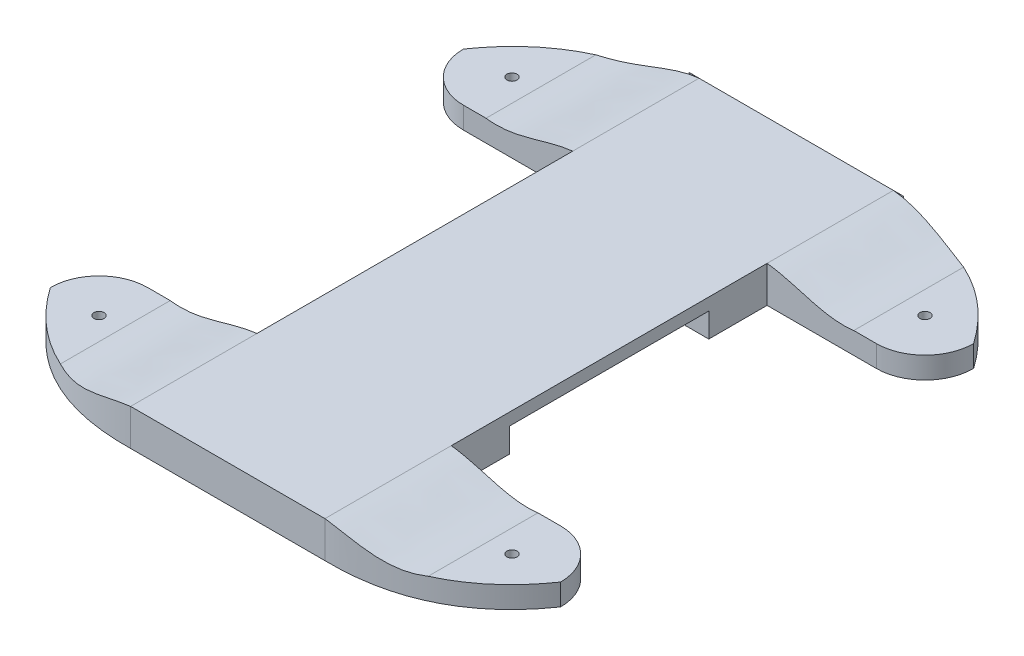
SolidWorks part; units mm, degrees
ref_plane "Front Plane" through (0, 0, 0) normal (0, 0, 1) x (1, 0, 0)
ref_plane "Top Plane" through (0, 0, 0) normal (0, 1, 0) x (1, 0, 0)
ref_plane "Right Plane" through (0, 0, 0) normal (1, 0, 0) x (0, 0, -1)
sketch "Sketch1" plane through (0, 0, 0) normal (0, 1, 0) x (1, 0, 0)
  line L0 (0, -315.44) -> (0, 409.5416) construction
  line L1 (383.7857, 0) -> (-378.4212, 0) construction
  line L2 (0, 0) -> (0, 117) construction
  line L7 (-85, 85) -> (-85, 105) construction
  line L9 (-40, 117) -> (40, 117)
  line L10 (-40, -117) -> (40, -117)
  line L12 (-85, 65) -> (-40, 65)
  line L13 (-85, -65) -> (-40, -65)
  line L14 (85, -65) -> (40, -65)
  line L15 (85, 65) -> (40, 65)
  line L16 (-40, 65) -> (-40, -65)
  line L17 (40, 65) -> (40, -65)
  circle A0 centre (-85, 85) radius 2.1
  circle A1 centre (85, 85) radius 2.1
  circle A2 centre (-85, -85) radius 2.1
  circle A3 centre (85, -85) radius 2.1
  arc A4 (-85, 65) -> (-105, 85) centre (-85, 85) cw
  arc A5 (-85, -65) -> (-105, -85) centre (-85, -85) ccw
  arc A6 (85, -65) -> (105, -85) centre (85, -85) cw
  arc A7 (85, 65) -> (105, 85) centre (85, 85) ccw
  spline S0 degree 2 poles (-105, 85) (-82.1988, 117.822) (-40, 117) knots 0 0 0 1 1 1
  spline S1 degree 2 poles (-105, -85) (-82.1988, -117.822) (-40, -117) knots 0 0 0 1 1 1
  spline S2 degree 2 poles (105, -85) (82.1988, -117.822) (40, -117) knots 0 0 0 1 1 1
  spline S3 degree 2 poles (105, 85) (82.1988, 117.822) (40, 117) knots 0 0 0 1 1 1
  point P7 (0, 0)
  point P23 (0, 117)
  dimension "D3" = 4.2
  dimension "D6" = 20
  dimension "D7" = 20
  dimension "D1" = 85
  dimension "D2" = 85
  dimension "D4" = 80
  dimension "D5" = 117
extrude "Boss-Extrude1" add sketch "Sketch1" along normal blind 15
sketch "Sketch2" plane through (0, 0, 0) normal (0, -1, 0) x (1, 0, 0)
  line L1 (41, -41) -> (-41, -41)
  line L2 (41, -41) -> (41, 41)
  line L3 (41, 41) -> (-41, 41)
  line L4 (-41, -41) -> (-41, 41)
  line L5 (41, -41) -> (-41, 41) construction
  line L6 (41, 41) -> (-41, -41) construction
  point P0 (0, 0)
  dimension "D1" = 82
extrude "Cut-Extrude1" cut sketch "Sketch2" against normal blind 10
sketch "Sketch3" plane through (0, 0, -117) normal (0, 0, -1) x (-1, 0, 0)
  line L0 (0, 0) -> (0, 64.527) construction
  line L1 (-75.6881, 8.8905) -> (-105, 8.8905)
  line L2 (-105, 15) -> (-105, 0) construction
  line L3 (-105, 8.8905) -> (-105, 15)
  line L4 (-105, 15) -> (-40, 15)
  line L5 (105, 15) -> (40, 15)
  line L6 (105, 8.8905) -> (105, 15)
  line L7 (75.6881, 8.8905) -> (105, 8.8905)
  spline S0 degree 3 poles (-75.6881, 8.8905) (-63.1283, 7.1873) (-52.0826, 13.6734) (-40, 15) knots 0 0 0 0 1 1 1 1
  spline S1 degree 3 poles (75.6881, 8.8905) (63.1283, 7.1873) (52.0826, 13.6734) (40, 15) knots 0 0 0 0 1 1 1 1
  point P13 (-59.8668, 10.2378)
extrude "Cut-Extrude2" cut sketch "Sketch3" against normal through all
